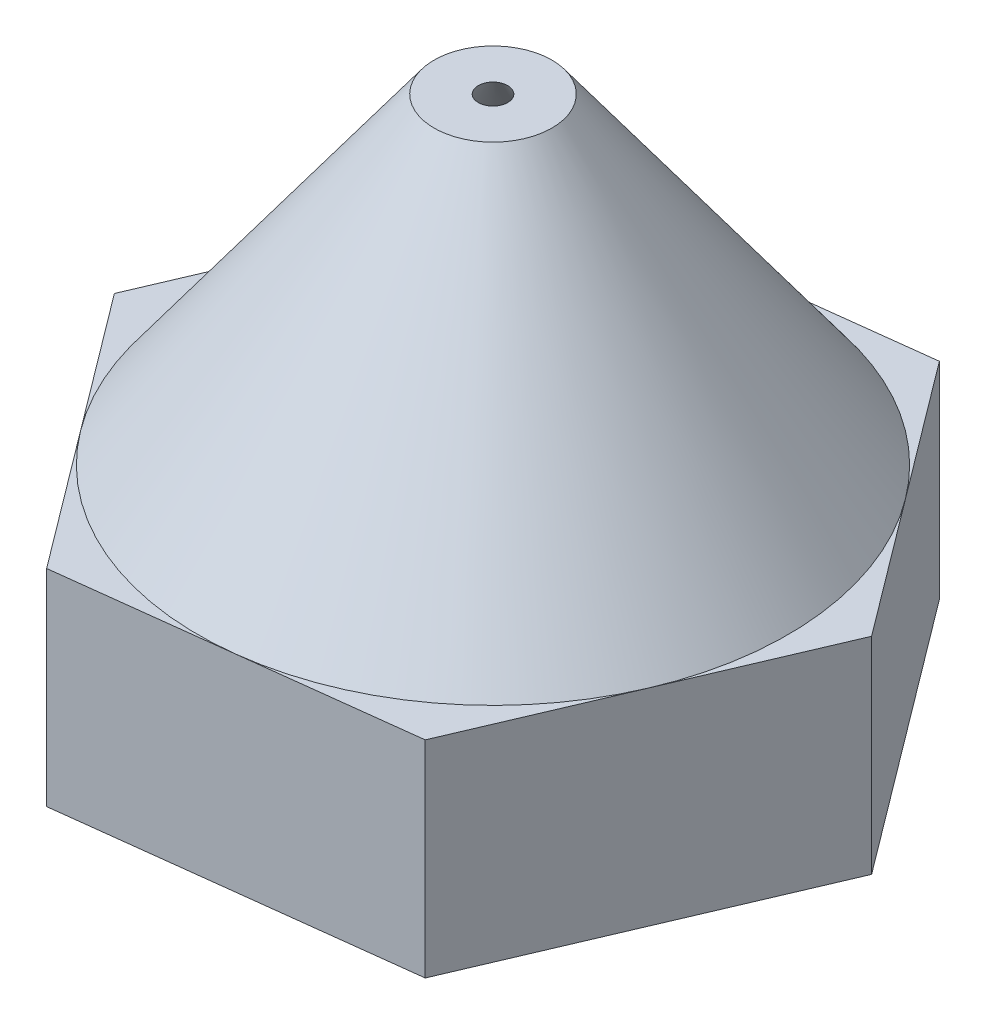
SolidWorks part; units mm, degrees
other "DetailItem1"
other "DetailItem2"
other "DetailItem3"
other "DetailItem4"
other "DetailItem5"
other "DetailItem6"
ref_plane "Front Plane" through (0, 0, 0) normal (0, 0, 1) x (1, 0, 0)
ref_plane "Top Plane" through (0, 0, 0) normal (0, 1, 0) x (1, 0, 0)
ref_plane "Right Plane" through (0, 0, 0) normal (1, 0, 0) x (0, 0, -1)
sketch "Sketch1" plane through (0, 0, 0) normal (0, 0, 1) x (1, 0, 0)
  line L0 (0, 0) -> (5, 0)
  line L1 (0, -3.7) -> (0, 5.45) construction
  line L2 (0, 5.45) -> (0, 0)
  line L3 (0, 5.45) -> (1, 5.45)
  line L4 (5, 0) -> (1, 5.45)
  dimension "D1" = 5
  dimension "D2" = 9.15
  dimension "D3" = 3.7
  dimension "D4" = 1
revolve "Revolve1" add sketch "Sketch1" angle 360 about L1
sketch "Sketch3" plane through (0, 0, 0) normal (0, 0, 1) x (1, 0, 0)
  line L0 (0, 0) -> (0, 3.4)
  line L1 (0, 3.4) -> (-1.65, 3.4)
  line L2 (-1.65, 3.4) -> (-1.65, 2.4)
  line L3 (0, 0) -> (-3, 0)
  line L4 (-1.65, 2.4) -> (-3, 0)
  line L5 (0, 3.4) -> (0, 5.45)
  line L6 (1, 5.45) -> (-1, 5.45) construction
  line L7 (-1.65, 3.4) -> (-0.25, 5.45)
  line L8 (-0.25, 5.45) -> (0, 5.45)
  dimension "D1" = 3.4
  dimension "D2" = 1.65
  dimension "D3" = 1
  dimension "D4" = 3
  dimension "D5" = 0.25
revolve "Cut-Revolve1" cut sketch "Sketch3" angle 360 about L0
sketch "Sketch10" plane through (0, 0, 0) normal (0, -1, 0) x (1, 0, 0)
  line L1 (5.7316, -0.6939) -> (3.4668, 4.6168)
  line L2 (3.4668, 4.6168) -> (-2.2649, 5.3107)
  line L3 (-2.2649, 5.3107) -> (-5.7316, 0.6939)
  line L4 (-5.7316, 0.6939) -> (-3.4668, -4.6168)
  line L5 (-3.4668, -4.6168) -> (2.2649, -5.3107)
  line L6 (2.2649, -5.3107) -> (5.7316, -0.6939)
  circle A0 centre (0, 0) radius 5 construction
  circle A1 centre (0, 0) radius 5 construction
  circle A2 centre (0, 0) radius 3
  dimension "D1" = 6
extrude "Boss-Extrude2" add sketch "Sketch10" along normal blind 3.5
